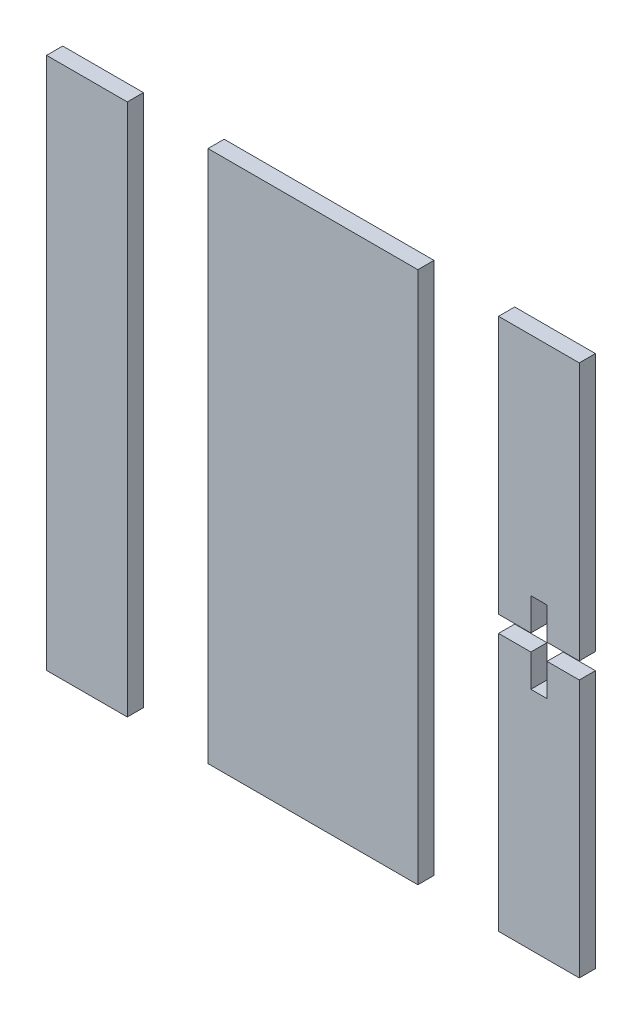
SolidWorks part; units mm, degrees
material "Wrought Copper"
ref_plane "Front Plane" through (0, 0, 0) normal (0, 0, 1) x (1, 0, 0)
ref_plane "Top Plane" through (0, 0, 0) normal (0, 1, 0) x (1, 0, 0)
ref_plane "Right Plane" through (0, 0, 0) normal (1, 0, 0) x (0, 0, -1)
sketch "Sketch1" plane through (0, 0, 0) normal (0, 0, 1) x (1, 0, 0)
  line L1 (3.035, 3.1791) -> (3.535, 3.1791)
  line L2 (3.035, 3.1791) -> (3.035, -0.1209)
  line L3 (1.235, 3.1791) -> (2.535, 3.1791)
  line L4 (3.035, -0.1209) -> (3.535, -0.1209)
  line L5 (1.235, 3.1791) -> (2.535, 3.1791)
  line L6 (1.235, 3.1791) -> (1.235, -0.1209)
  line L7 (1.235, -0.1209) -> (2.535, -0.1209)
  line L8 (2.535, 3.1791) -> (2.535, -0.1209)
  line L9 (3.535, 3.1791) -> (3.535, -0.1209)
  line L10 (0.235, 3.1791) -> (0.735, 3.1791)
  line L11 (0.235, 3.1791) -> (0.235, -0.1209)
  line L12 (0.235, -0.1209) -> (0.735, -0.1209)
  line L13 (0.735, 3.1791) -> (0.735, -0.1209)
  dimension "D1" = 3.3
  dimension "D2" = 0.5
  dimension "D3" = 1.3
  dimension "D4" = 0.5
  dimension "D5" = 3.3
extrude "Boss-Extrude1" add sketch "Sketch1" along normal blind 0.1 contours L13 L10 L11 L12 | L8 L3 L6 L7 | L9 L1 L2 L4
sketch "Sketch3" plane through (0, 0, 0.1) normal (0, 0, 1) x (1, 0, 0)
  line L1 (3.035, 1.5802) -> (3.235, 1.5802)
  line L2 (3.035, 1.5802) -> (3.035, 1.478)
  line L3 (3.035, 1.478) -> (3.235, 1.478)
  line L4 (3.535, 1.5802) -> (3.535, 1.478)
  line L6 (3.235, 1.478) -> (3.235, 1.278)
  line L7 (3.235, 1.7802) -> (3.335, 1.7802)
  line L8 (3.235, 1.7802) -> (3.235, 1.5802)
  line L9 (3.235, 1.278) -> (3.335, 1.278)
  line L10 (3.335, 1.7802) -> (3.335, 1.5802)
  line L11 (3.335, 1.478) -> (3.335, 1.278)
  line L12 (3.335, 1.5802) -> (3.535, 1.5802)
  line L13 (3.335, 1.478) -> (3.535, 1.478)
  line L14 (0.235, 3.1791) -> (0.235, -0.1209) construction
  line L15 (3.035, 1.5291) -> (0.3797, 1.5291) construction
  line L16 (0.235, 1.5291) -> (0.3572, 1.5291) construction
  line L17 (3.535, 3.1791) -> (3.535, -0.1209) construction
  line L18 (3.035, 3.1791) -> (3.035, -0.1209) construction
  dimension "D1" = 0.1023
  dimension "D2" = 0.1
extrude "Cut-Extrude1" cut sketch "Sketch3" against normal through all
